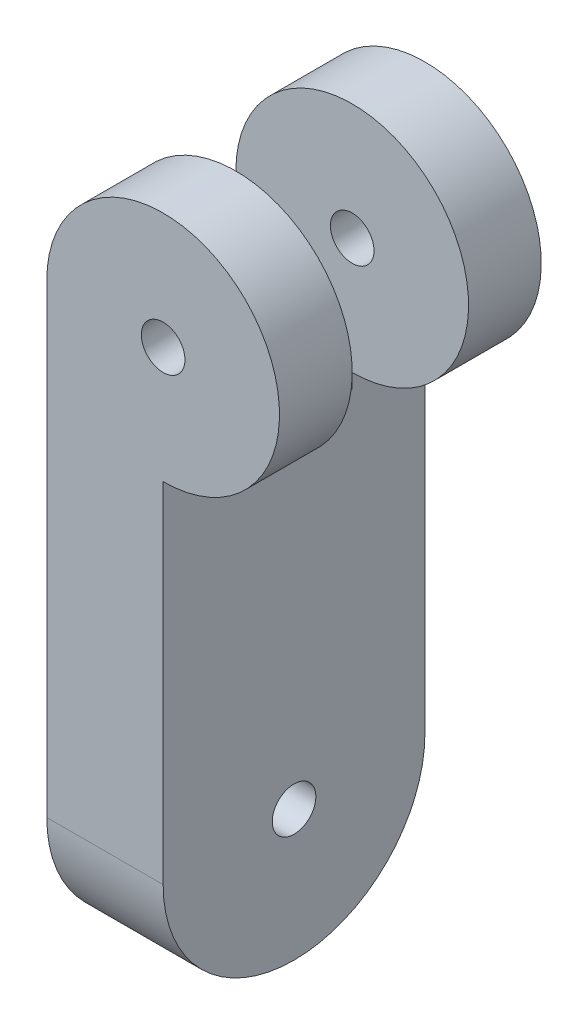
SolidWorks part; units mm, degrees
ref_plane "Front" through (0, 0, 0) normal (0, 0, 1) x (1, 0, 0)
ref_plane "Top" through (0, 0, 0) normal (0, 1, 0) x (1, 0, 0)
ref_plane "Right" through (0, 0, 0) normal (1, 0, 0) x (0, 0, -1)
sketch "草图1" plane through (0, 0, 0) normal (1, 0, 0) x (0, 0, -1)
  line L2 (-18, 0) -> (-18, 80)
  line L3 (-18, 80) -> (18, 80)
  line L4 (18, 0) -> (18, 80)
  arc A0 (-18, 0) -> (18, 0) centre (0, 0) ccw
  circle A1 centre (0, 0) radius 3
  dimension "D1" = 80
extrude "凸台-拉伸1" add sketch "草图1" along normal blind 16
sketch "草图3" plane through (0, 0, -18) normal (0, 0, -1) x (-1, 0, 0)
  line L1 (-16, 80) -> (-32, 80)
  line L2 (-16, 80) -> (-16, 48)
  line L3 (-16, 48) -> (-32, 48)
  line L4 (-32, 80) -> (-32, 48)
  dimension "D1" = 16
  dimension "D2" = 32
extrude "凸台-拉伸2" add sketch "草图3" against normal blind 36
sketch "草图5" plane through (0, 0, -18) normal (0, 0, -1) x (-1, 0, 0)
  line L0 (-16, 92.9961) -> (8.9928, 92.9961)
  line L1 (-16, 92.9961) -> (-49.1174, 92.9961)
  line L2 (-49.1174, 92.9961) -> (-49.1174, 39.0011)
  line L3 (-49.1174, 39.0011) -> (-16, 39.0011)
  line L4 (-16, 0) -> (-16, 48) construction
  line L5 (-16, 39.0011) -> (-16, 48)
  line L6 (8.9928, 92.9961) -> (8.9928, 64)
  line L7 (8.9928, 64) -> (0, 64)
  arc A0 (0, 64) -> (-16, 48) centre (-16, 64) ccw
  circle A1 centre (-16, 64) radius 3
extrude "切除-拉伸1" cut sketch "草图5" against normal blind 36
sketch "草图8" plane through (0, 0, 0) normal (0, 0, 1) x (1, 0, 0)
  circle A0 centre (16, 64) radius 18
extrude "切除-拉伸6" cut sketch "草图8" against normal mid plane 16
